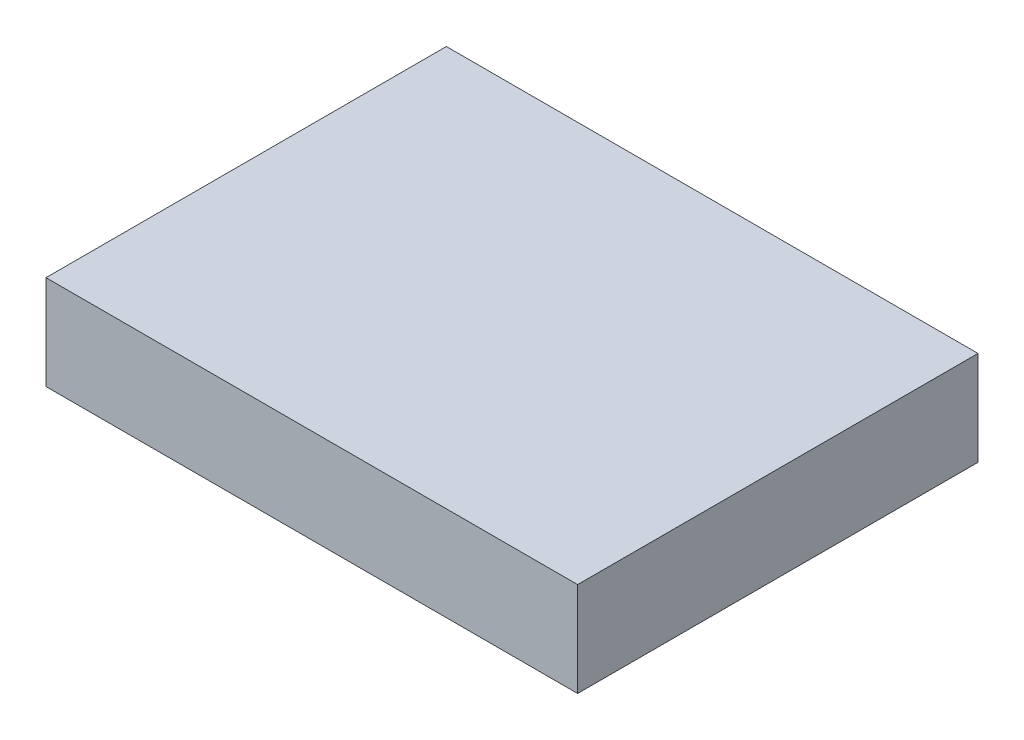
SolidWorks part; units mm, degrees
ref_plane "Front Plane" through (0, 0, 0) normal (0, 0, 1) x (1, 0, 0)
ref_plane "Top Plane" through (0, 0, 0) normal (0, 1, 0) x (1, 0, 0)
ref_plane "Right Plane" through (0, 0, 0) normal (1, 0, 0) x (0, 0, -1)
sketch "Sketch1" plane through (0, 0, 0) normal (0, 1, 0) x (1, 0, 0)
  line L1 (26.4921, 31.8469) -> (116.6779, 31.8469)
  line L2 (26.4921, 31.8469) -> (26.4921, -36.0743)
  line L3 (26.4921, -36.0743) -> (116.6779, -36.0743)
  line L4 (116.6779, 31.8469) -> (116.6779, -36.0743)
extrude "Boss-Extrude1" add sketch "Sketch1" along normal blind 16
